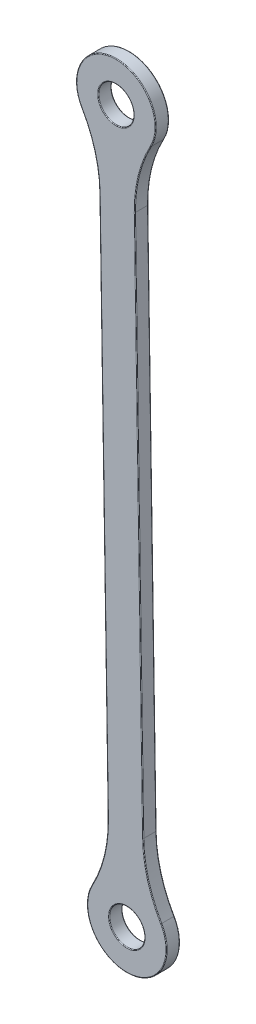
SolidWorks part; units mm, degrees
ref_plane "Front Plane" through (0, 0, 0) normal (0, 0, 1) x (1, 0, 0)
ref_plane "Top Plane" through (0, 0, 0) normal (0, 1, 0) x (1, 0, 0)
ref_plane "Right Plane" through (0, 0, 0) normal (1, 0, 0) x (0, 0, -1)
sketch "Sketch1" plane through (0, 0, 0) normal (0, 0, 1) x (1, 0, 0)
  line L0 (33.78, 57.2783) -> (31.312, 217.2593) construction
  line L1 (33.78, 57.2783) -> (31.312, 217.2593) construction
sketch "Sketch2" plane through (0, 0, 0) normal (0, 0, 1) x (1, 0, 0)
  line L0 (33.78, 57.2783) -> (31.312, 217.2593) construction
  line L1 (33.78, 57.2783) -> (31.312, 217.2593) construction
  line L2 (29.7805, 57.2166) -> (27.3125, 217.1976)
  line L3 (37.7795, 57.34) -> (35.3115, 217.321)
  circle A0 centre (31.312, 217.2593) radius 9
  circle A1 centre (33.78, 57.2783) radius 9
  arc A2 (29.7805, 57.2166) -> (37.7795, 57.34) centre (33.78, 57.2783) ccw
  arc A3 (35.3115, 217.321) -> (27.3125, 217.1976) centre (31.312, 217.2593) ccw
  arc A4 (27.3125, 217.1976) -> (35.3115, 217.321) centre (31.312, 217.2593) ccw
  arc A5 (29.7805, 57.2166) -> (37.7795, 57.34) centre (33.78, 57.2783) cw
  point P7 (32.546, 137.2688)
  dimension "D1" = 18
  dimension "D2" = 4
extrude "Boss-Extrude1" add sketch "Sketch2" against normal blind 3 contours A3 L3 A0 L2 | L0 A0 L3 A4 | A0 L0 A4 L2 | A1 L0 A0 L2 | L0 A1 L3 A0 | A2 L2 A1 L3 | L0 A5 L3 A1 | A5 L0 A1 L2
fillet "Fillet1" radius 30 4 edges at (29.6561, 65.2779, -1.5) (37.6552, 65.4013, -1.5) (35.4359, 209.2597, -1.5) (27.4368, 209.1363, -1.5)
fillet "Fillet2" radius 0.15 20 edges at (37.78, 57.2783, -3) (37.78, 57.2783, 0) (35.312, 217.2593, -3) (35.312, 217.2593, 0) (38.5793, 68.8632, -3) (38.5793, 68.8632, 0) (36.5455, 137.3305, 0) (36.5455, 137.3305, -3) (36.4664, 205.828, -3) (36.4664, 205.828, 0) (31.1732, 226.2582, 0) (31.1732, 226.2582, -3) (26.5127, 205.6745, -3) (26.5127, 205.6745, 0) (28.5465, 137.2071, -3) (28.5465, 137.2071, 0) (28.6256, 68.7096, -3) (28.6256, 68.7096, 0) (33.9188, 48.2794, 0) (33.9188, 48.2794, -3)
